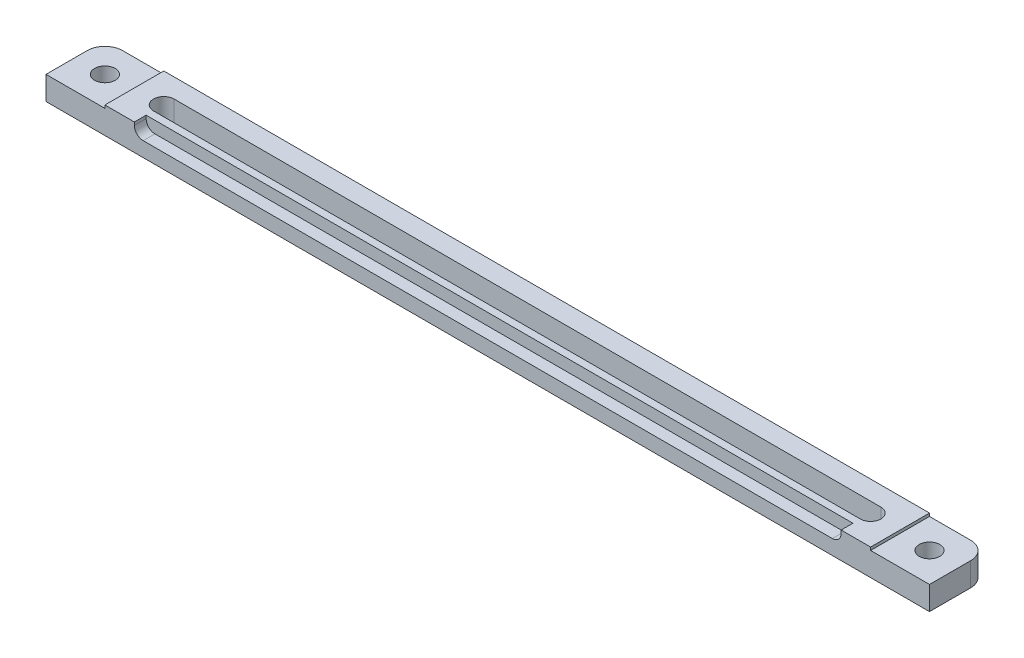
SolidWorks part; units mm, degrees
ref_plane "Front Plane" through (0, 0, 0) normal (0, 0, 1) x (1, 0, 0)
ref_plane "Top Plane" through (0, 0, 0) normal (0, 1, 0) x (1, 0, 0)
ref_plane "Right Plane" through (0, 0, 0) normal (1, 0, 0) x (0, 0, -1)
sketch "Sketch1" plane through (0, 0, 0) normal (0, 1, 0) x (1, 0, 0)
  line L1 (72, 5) -> (-72, 5)
  line L2 (75, 2) -> (75, -5)
  line L3 (75, -5) -> (-75, -5)
  line L4 (-75, 2) -> (-75, -5)
  line L5 (75, 5) -> (-75, -5) construction
  line L6 (75, -5) -> (-75, 5) construction
  line L7 (60, -1.75) -> (-60, -1.75)
  line L8 (60, -1.75) -> (60, 1.75)
  line L9 (60, 1.75) -> (-60, 1.75)
  line L10 (-60, -1.75) -> (-60, 1.75)
  line L11 (60, -1.75) -> (-60, 1.75) construction
  line L12 (60, 1.75) -> (-60, -1.75) construction
  circle A0 centre (-70, 0) radius 1.75
  circle A1 centre (70, 0) radius 1.75
  arc A2 (75, 2) -> (72, 5) centre (72, 2) ccw
  arc A3 (-72, 5) -> (-75, 2) centre (-72, 2) ccw
  circle A4 centre (-60, 0) radius 1.75
  circle A5 centre (60, 0) radius 1.75
  point P0 (0, 0)
  point P16 (0, 0)
  dimension "D3" = 3.5
  dimension "D6" = 3.5
  dimension "D9" = 3
  dimension "D10" = 3
  dimension "D1" = 10
  dimension "D2" = 150
  dimension "D4" = 5
  dimension "D5" = 5
  dimension "D7" = 5
  dimension "D8" = 5
  dimension "D11" = 3.5
  dimension "D12" = 120
extrude "Boss-Extrude1" add sketch "Sketch1" along normal blind 4 contours L1 A3 L4 L3 L2 A2 A5 L7 A4 L9 A0 A1
sketch "Sketch2" plane through (0, 4, 0) normal (0, 1, 0) x (1, 0, 0)
  line L0 (72, 5) -> (-72, 5) construction
  line L1 (-65, 5) -> (65, 5)
  line L2 (-65, 5) -> (-65, -5)
  line L3 (-65, -5) -> (65, -5)
  line L4 (65, 5) -> (65, -5)
  line L5 (75, -5) -> (-75, -5) construction
  line L6 (-75, 2) -> (-75, -5) construction
  line L7 (75, 2) -> (75, -5) construction
  line L12 (72, 5) -> (-72, 5)
  line L13 (-75, 2) -> (-75, -5)
  line L14 (-75, -5) -> (75, -5)
  line L15 (75, -5) -> (75, 2)
  line L16 (72, 5) -> (-72, 5)
  line L17 (-75, 2) -> (-75, -5)
  line L18 (-75, -5) -> (75, -5)
  line L19 (75, -5) -> (75, 2)
  arc A2 (-72, 5) -> (-75, 2) centre (-72, 2) ccw
  arc A3 (75, 2) -> (72, 5) centre (72, 2) ccw
  arc A4 (-72, 5) -> (-75, 2) centre (-72, 2) ccw
  arc A5 (75, 2) -> (72, 5) centre (72, 2) ccw
  arc M11 (60, 1.75) -> (60, -1.75) centre (60, 0) cw
  line M12 (60, -1.75) -> (-60, -1.75)
  arc M13 (-60, -1.75) -> (-60, 1.75) centre (-60, 0) cw
  line M14 (-60, 1.75) -> (60, 1.75)
  line M17 (72, 5) -> (-72, 5)
  line M20 (-75, -5) -> (75, -5)
  dimension "D1" = 10
  dimension "D2" = 10
  dimension "D3" = 0
extrude "Boss-Extrude2" add sketch "Sketch2" along normal blind 0.5 contours L4 L2 M17 M20 M14 M11 M12 M13
sketch "Sketch3" plane through (0, 0, 5) normal (0, 0, 1) x (1, 0, 0)
  line L0 (0, 4.5) -> (0, 0) construction
  line L7 (-65, 4.5) -> (65, 4.5) construction
  line L9 (-58.5, 2.5) -> (58.5, 2.5)
  line L10 (-60, 4) -> (-60, 4.5)
  line L11 (-60, 4.5) -> (60, 4.5)
  line L12 (60, 4) -> (60, 4.5)
  line L13 (-60, 2.5) -> (60, 4.5) construction
  line L14 (-60, 4.5) -> (60, 2.5) construction
  arc A2 (58.5, 2.5) -> (60, 4) centre (58.5, 4) ccw
  arc A3 (-60, 4) -> (-58.5, 2.5) centre (-58.5, 4) ccw
  point P5 (0, 3.5)
  dimension "D3" = 1.5
  dimension "D4" = 1.5
  dimension "D1" = 2
  dimension "D2" = 120
extrude "Cut-Extrude1" cut sketch "Sketch3" against normal blind 2
